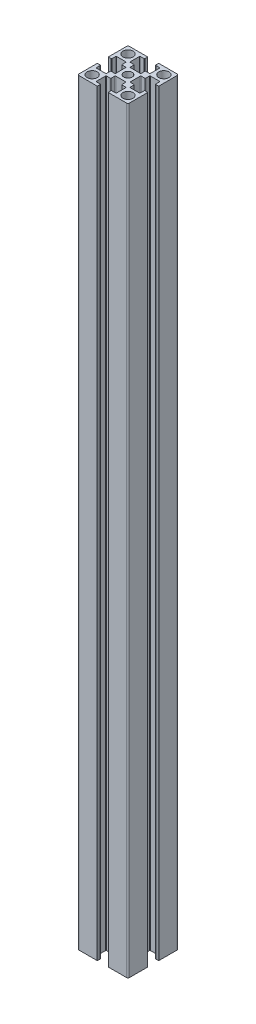
SolidWorks part; units mm, degrees
ref_plane "前视基准面" through (0, 0, 0) normal (0, 0, 1) x (1, 0, 0)
ref_plane "上视基准面" through (0, 0, 0) normal (0, 1, 0) x (1, 0, 0)
ref_plane "右视基准面" through (0, 0, 0) normal (1, 0, 0) x (0, 0, -1)
other "Configuration Table"
sketch "草图1" plane through (0, 0, 0) normal (0, 1, 0) x (1, 0, 0)
  line L0 (0, 46.1728) -> (0, -33.2059) construction
  line L1 (-46.4356, 0) -> (43.8072, 0) construction
  line L2 (0, 0) -> (-14.2, 14.2) construction
  line L3 (-9.5, 10) -> (-2.15, 10)
  line L4 (-2.15, 10) -> (-2.15, 8.7)
  line L5 (-2.15, 8.7) -> (-4, 8.7)
  line L6 (-4, 8.7) -> (-4, 4.7)
  line L7 (-4, 4.7) -> (-2.15, 4.7)
  line L8 (-2.15, 4.7) -> (-2.15, 2.9)
  line L9 (-2.15, 2.9) -> (0, 2.9)
  line L10 (-2.9, 2.15) -> (-2.9, 0)
  line L11 (-4.7, 2.15) -> (-2.9, 2.15)
  line L12 (-4.7, 4) -> (-4.7, 2.15)
  line L13 (-8.7, 4) -> (-4.7, 4)
  line L14 (-8.7, 2.15) -> (-8.7, 4)
  line L15 (-10, 2.15) -> (-8.7, 2.15)
  line L16 (-10, 9.5) -> (-10, 2.15)
  line L17 (9.5, 10) -> (2.15, 10)
  line L18 (10, 9.5) -> (10, 2.15)
  line L19 (10, 2.15) -> (8.7, 2.15)
  line L20 (8.7, 2.15) -> (8.7, 4)
  line L21 (8.7, 4) -> (4.7, 4)
  line L22 (4.7, 4) -> (4.7, 2.15)
  line L23 (4.7, 2.15) -> (2.9, 2.15)
  line L24 (2.9, 2.15) -> (2.9, 0)
  line L25 (2.15, 10) -> (2.15, 8.7)
  line L26 (2.15, 8.7) -> (4, 8.7)
  line L27 (4, 8.7) -> (4, 4.7)
  line L28 (4, 4.7) -> (2.15, 4.7)
  line L29 (2.15, 4.7) -> (2.15, 2.9)
  line L30 (2.15, 2.9) -> (0, 2.9)
  line L31 (10, -9.5) -> (10, -2.15)
  line L32 (9.5, -10) -> (2.15, -10)
  line L33 (2.15, -10) -> (2.15, -8.7)
  line L34 (2.15, -8.7) -> (4, -8.7)
  line L35 (4, -8.7) -> (4, -4.7)
  line L36 (4, -4.7) -> (2.15, -4.7)
  line L37 (2.15, -4.7) -> (2.15, -2.9)
  line L38 (2.15, -2.9) -> (0, -2.9)
  line L39 (10, -2.15) -> (8.7, -2.15)
  line L40 (8.7, -2.15) -> (8.7, -4)
  line L41 (8.7, -4) -> (4.7, -4)
  line L42 (4.7, -4) -> (4.7, -2.15)
  line L43 (4.7, -2.15) -> (2.9, -2.15)
  line L44 (2.9, -2.15) -> (2.9, 0)
  line L45 (-9.5, -10) -> (-2.15, -10)
  line L46 (-10, -9.5) -> (-10, -2.15)
  line L47 (-10, -2.15) -> (-8.7, -2.15)
  line L48 (-8.7, -2.15) -> (-8.7, -4)
  line L49 (-8.7, -4) -> (-4.7, -4)
  line L50 (-4.7, -4) -> (-4.7, -2.15)
  line L51 (-4.7, -2.15) -> (-2.9, -2.15)
  line L52 (-2.9, -2.15) -> (-2.9, 0)
  line L53 (-2.15, -10) -> (-2.15, -8.7)
  line L54 (-2.15, -8.7) -> (-4, -8.7)
  line L55 (-4, -8.7) -> (-4, -4.7)
  line L56 (-4, -4.7) -> (-2.15, -4.7)
  line L57 (-2.15, -4.7) -> (-2.15, -2.9)
  line L58 (-2.15, -2.9) -> (0, -2.9)
  circle A0 centre (-7.1, 7.1) radius 2
  circle A1 centre (7.1, 7.1) radius 2
  circle A2 centre (7.1, -7.1) radius 2
  circle A3 centre (-7.1, -7.1) radius 2
  circle A4 centre (0, 0) radius 1.65
  arc A5 (-10, -9.5) -> (-9.5, -10) centre (-9.5, -9.5) ccw
  arc A6 (9.5, -10) -> (10, -9.5) centre (9.5, -9.5) ccw
  arc A7 (10, 9.5) -> (9.5, 10) centre (9.5, 9.5) ccw
  arc A8 (-9.5, 10) -> (-10, 9.5) centre (-9.5, 9.5) ccw
  point P78 (0, 0)
  point P81 (-10, 10)
  dimension "D2" = 4
  dimension "D12" = 3.3
  dimension "D13" = 0.5
  dimension "D1" = 45
  dimension "D3" = 10
  dimension "D4" = 4.3
  dimension "D5" = 8
  dimension "D6" = 4.3
  dimension "D7" = 14.2
  dimension "D8" = 1.3
  dimension "D9" = 5.3
  dimension "D10" = 7.1
  dimension "D11" = 4
extrude "凸台-拉伸1" add sketch "草图1" along normal blind 300
fillet "圆角1" radius 0.2 48 edges at (-2.15, 150, -8.7) (-4, 150, -8.7) (-4, 150, -4.7) (-2.15, 150, -4.7) (-2.15, 150, -2.9) (2.15, 150, -2.9) (2.15, 150, -4.7) (4, 150, -4.7) (4, 150, -8.7) (2.15, 150, -8.7) (2.15, 150, -10) (10, 150, -2.15) (8.7, 150, -2.15) (8.7, 150, -4) (4.7, 150, -4) (4.7, 150, -2.15) (2.9, 150, -2.15) (2.9, 150, 2.15) (4.7, 150, 2.15) (4.7, 150, 4) (8.7, 150, 4) (8.7, 150, 2.15) (10, 150, 2.15) (2.15, 150, 8.7) (4, 150, 8.7) (4, 150, 4.7) (2.15, 150, 4.7) (2.15, 150, 2.9) (-2.15, 150, 2.9) (-2.15, 150, 4.7) (-4, 150, 4.7) (-4, 150, 8.7) (-2.15, 150, 8.7) (-2.15, 150, 10) (-10, 150, 2.15) (-8.7, 150, 4) (-4.7, 150, 4) (-4.7, 150, 2.15) (-2.9, 150, 2.15) (-2.9, 150, -2.15) (-4.7, 150, -2.15) (-4.7, 150, -4) (-8.7, 150, -4) (-8.7, 150, -2.15) (-10, 150, -2.15) (-2.15, 150, -10) (-8.7, 150, 2.15) (2.15, 150, 10)
